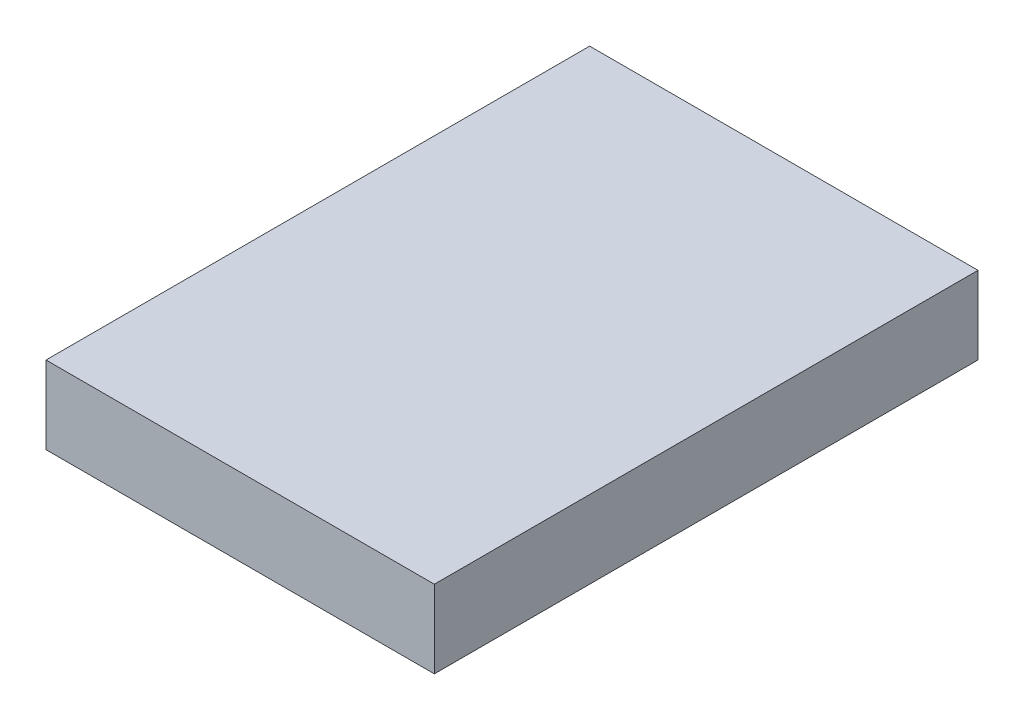
SolidWorks part; units mm, degrees
ref_plane "前视基准面" through (0, 0, 0) normal (0, 0, 1) x (1, 0, 0)
ref_plane "上视基准面" through (0, 0, 0) normal (0, 1, 0) x (1, 0, 0)
ref_plane "右视基准面" through (0, 0, 0) normal (1, 0, 0) x (0, 0, -1)
sketch "草图1" plane through (0, 0, 0) normal (0, 1, 0) x (1, 0, 0)
  line L1 (-15, 21) -> (15, 21)
  line L2 (-15, 21) -> (-15, -21)
  line L3 (-15, -21) -> (15, -21)
  line L4 (15, 21) -> (15, -21)
  line L5 (-15, 21) -> (15, -21) construction
  line L6 (-15, -21) -> (15, 21) construction
  point P0 (0, 0)
  dimension "D1" = 42
  dimension "D2" = 30
extrude "凸台-拉伸1" add sketch "草图1" along normal blind 6
ref_plane "基准面1" through (0, 3, 0) normal (0, 1, 0) x (1, 0, 0)
